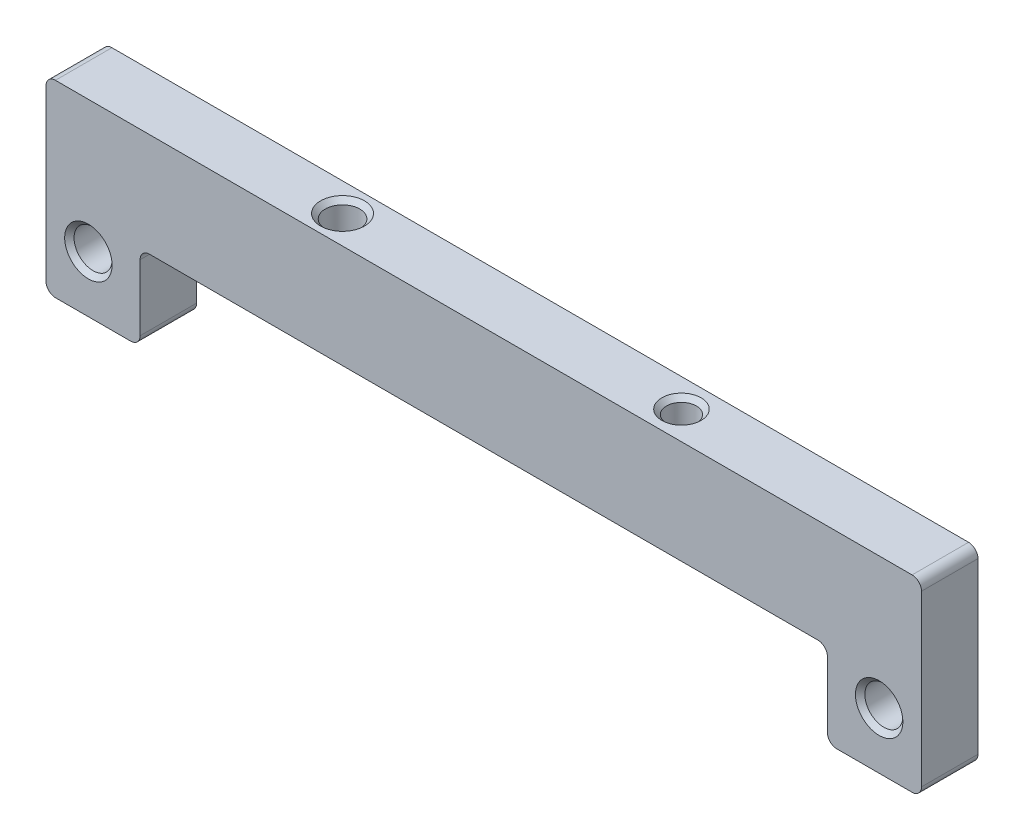
SolidWorks part; units mm, degrees
material "6063-T1"
ref_plane "Front" through (0, 0, 0) normal (0, 0, 1) x (1, 0, 0)
ref_plane "Top" through (0, 0, 0) normal (0, 1, 0) x (1, 0, 0)
ref_plane "Right" through (0, 0, 0) normal (1, 0, 0) x (0, 0, -1)
sketch "Sketch1" plane through (0, 0, 0) normal (0, 0, 1) x (1, 0, 0)
  line L1 (-46.5, -10) -> (46.5, -10)
  line L2 (-46.5, -10) -> (-46.5, 10)
  line L3 (-46.5, 10) -> (46.5, 10)
  line L4 (46.5, -10) -> (46.5, 10)
  line L5 (-46.5, -10) -> (46.5, 10) construction
  line L6 (-46.5, 10) -> (46.5, -10) construction
  point P0 (0, 0)
  dimension "D1" = 20
  dimension "D2" = 93
extrude "Boss-Extrude1" add sketch "Sketch1" along normal blind 6
ref_plane "Plane1" through (0, 0, 0) normal (1, 0, 0) x (0, 0, -1)
sketch "Sketch3" plane through (0, 0, 6) normal (0, 0, 1) x (1, 0, 0)
  line L0 (0, 0) -> (0, 50000) construction
  line L1 (-46.5, -10) -> (46.5, -10) construction
  line L2 (-36.5, -10) -> (36.5, -10)
  line L3 (-36.5, -10) -> (-36.5, -1)
  line L4 (-36.5, -1) -> (36.5, -1)
  line L5 (36.5, -10) -> (36.5, -1)
  line L6 (-46.5, 10) -> (-46.5, -10) construction
  dimension "D1" = 10
  dimension "D2" = 9
extrude "Cut-Extrude2" cut sketch "Sketch3" against normal up to next
chamfer "Chamfer1" [suppressed] distance 1.5 angle 60
hole_wizard "#6 Clearance Hole1" positions "Sketch4" profile "Sketch5" hole size "#6" standard "ANSI Inch" end condition through all
sketch "Sketch4" plane through (0, -1, 0) normal (0, -1, 0) x (-1, 0, 0)
  line L0 (0, 5.4739) -> (0, 14.5695) construction
  line L1 (46.5, -6) -> (46.5, 0) construction
  point P0 (18, -3)
  point P13 (46.5, -3)
  point P14 (0, 0)
  dimension "D1" = 18
sketch "Sketch5" plane through (-18, -1, 3) normal (1, 0, 0) x (0, 0, -1)
  line L0 (0, 0) -> (0, 11)
  line L1 (0, 11) -> (1.8288, 11)
  line L2 (1.8288, 11) -> (1.8288, 0)
  line L5 (1.8288, 0) -> (0, 0)
  line L11 (0, -6.35) -> (0, 107.95) construction
  dimension "Thru Hole Dia." = 3.6576
  dimension "Thru Hole Depth" = 11
hole_wizard "Tap Drill for #10-32 Tap1" positions "Sketch6" profile "Sketch7" hole size "#10-32" standard "ANSI Inch" end condition through all
sketch "Sketch6" plane through (0, 0, 6) normal (0, 0, 1) x (1, 0, 0)
  line L0 (0, -4.4217) -> (0, -17.6703) construction
  line L1 (-46.5, -10) -> (-36.5, -10) construction
  point P0 (-42, -4)
  point P2 (42, -4)
  dimension "D1" = 84
  dimension "D2" = 6
sketch "Sketch7" plane through (-42, -4, 6) normal (1, 0, 0) x (0, -1, 0)
  line L0 (0, 0) -> (0, 6)
  line L1 (0, 6) -> (2.0193, 6)
  line L2 (2.0193, 6) -> (2.0193, 0)
  line L5 (2.0193, 0) -> (0, 0)
  line L11 (0, -6.35) -> (0, 107.95) construction
  dimension "Thru Hole Dia." = 4.0386
  dimension "Thru Hole Depth" = 6
hole_wizard "1/8 (0.125) Diameter Hole1" positions "Sketch8" profile "Sketch9" hole size "1/8" standard "ANSI Inch" end condition through all
sketch "Sketch8" plane through (0, -1, 0) normal (0, -1, 0) x (-1, 0, 0)
  circle A0 centre (18, -3) radius 1.8288 construction
  circle A1 centre (18, -3) radius 1.8288
  point P0 (-18, -3)
  point P6 (0, 0)
  point P7 (0, 0)
  dimension "D1" = 18
sketch "Sketch9" plane through (18, -1, 3) normal (1, 0, 0) x (0, 0, -1)
  line L0 (0, 0) -> (0, 11)
  line L1 (0, 11) -> (1.5875, 11)
  line L2 (1.5875, 11) -> (1.5875, 0)
  line L5 (1.5875, 0) -> (0, 0)
  line L11 (0, -6.35) -> (0, 107.95) construction
  dimension "Thru Hole Dia." = 3.175
  dimension "Thru Hole Depth" = 11
fillet "Fillet1" radius 1 8 edges at (-46.5, -10, 3) (-46.5, 10, 3) (46.5, -10, 3) (36.5, -10, 3) (36.5, -1, 3) (-36.5, -1, 3) (-36.5, -10, 3) (46.5, 10, 3)
chamfer "Chamfer2" distance 0.5 angle 45 8 edges at (44.0193, -4, 6) (44.0193, -4, 0) (-39.9807, -4, 6) (-39.9807, -4, 0) (-18, -1, 1.1712) (-18, 10, 1.1712) (18, -1, 1.4125) (18, 10, 1.4125)
